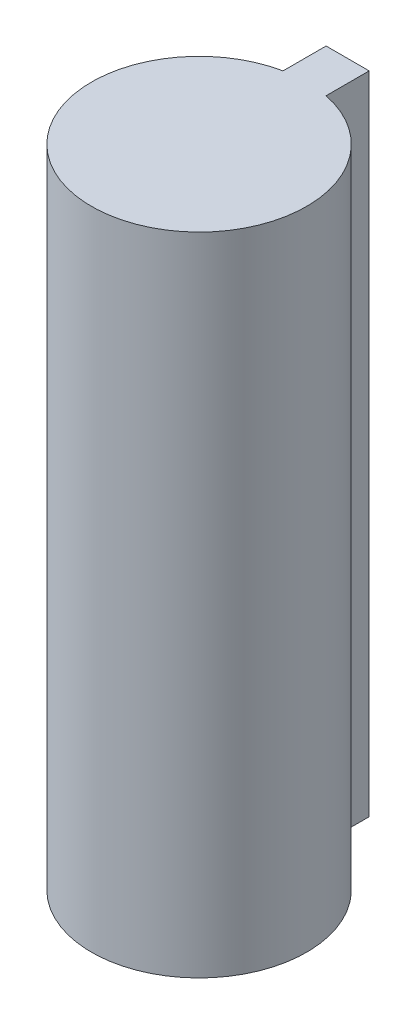
SolidWorks part; units mm, degrees
ref_plane "前视基准面" through (0, 0, 0) normal (0, 0, 1) x (1, 0, 0)
ref_plane "上视基准面" through (0, 0, 0) normal (0, 1, 0) x (1, 0, 0)
ref_plane "右视基准面" through (0, 0, 0) normal (1, 0, 0) x (0, 0, -1)
sketch "草图1" plane through (0, 0, 0) normal (0, 1, 0) x (1, 0, 0)
  line L1 (0, -6.6512) -> (0, 18.474) construction
  line L2 (-2, 9.798) -> (-2, 13.798)
  line L3 (-2, 13.798) -> (2, 13.798)
  line L4 (2, 9.798) -> (2, 13.798)
  arc A0 (-2, 9.798) -> (2, 9.798) centre (0, 0) ccw
  point P10 (0, 13.798)
  dimension "D1" = 4
  dimension "D3" = 10
  dimension "D2" = 4
extrude "凸台-拉伸1" add sketch "草图1" along normal blind 60
